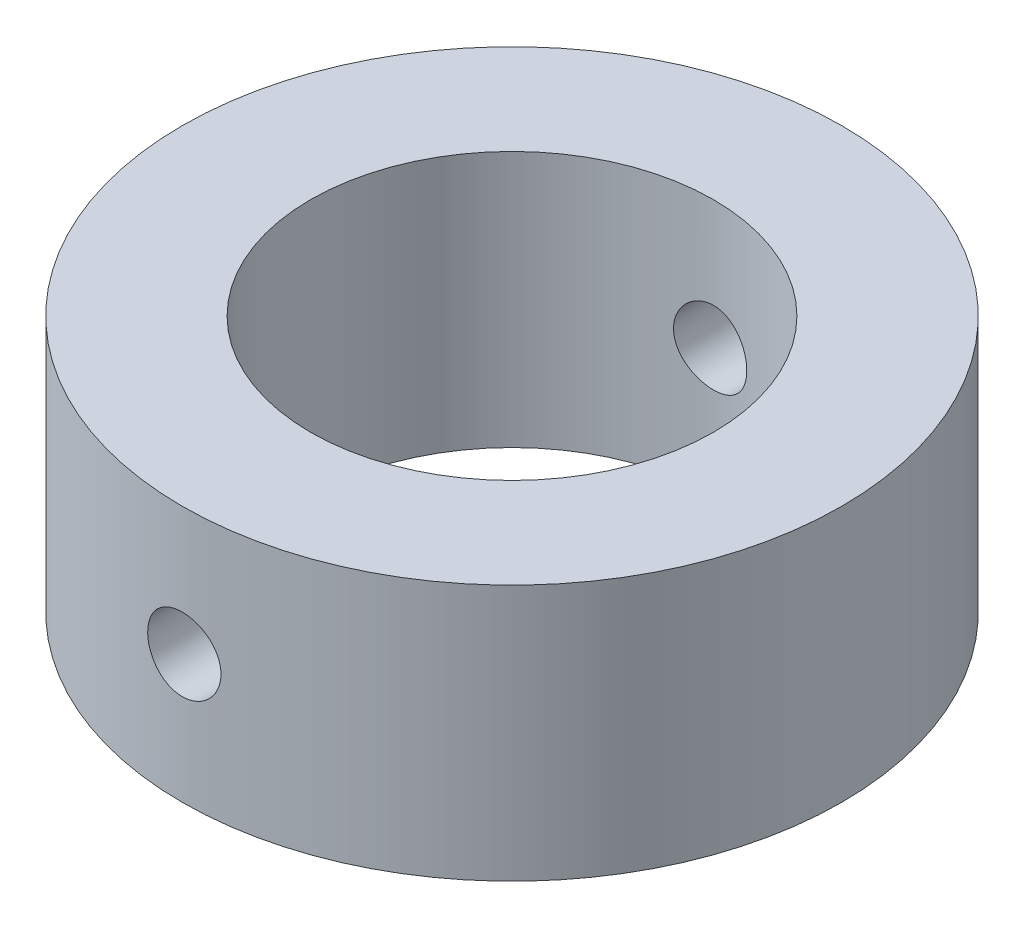
SolidWorks part; units mm, degrees
ref_plane "Front Plane" through (0, 0, 0) normal (0, 0, 1) x (1, 0, 0)
ref_plane "Top Plane" through (0, 0, 0) normal (0, 1, 0) x (1, 0, 0)
ref_plane "Right Plane" through (0, 0, 0) normal (1, 0, 0) x (0, 0, -1)
sketch "Sketch1" plane through (0, 0, 0) normal (0, 0, 1) x (1, 0, 0)
  line L0 (-2.184, 0) -> (25.368, 0) construction
  line L1 (0, -7.728) -> (0, 16.688) construction
  line L3 (18, -7) -> (11, -7)
  line L4 (18, -7) -> (18, 7)
  line L5 (18, 7) -> (11, 7)
  line L6 (11, -7) -> (11, 7)
  line L7 (18, -7) -> (11, 7) construction
  line L8 (18, 7) -> (11, -7) construction
  point P5 (14.5, 0)
  dimension "D1" = 14
  dimension "D2" = 18
  dimension "D3" = 11
revolve "Revolve1" add sketch "Sketch1" angle 360 about L1
sketch "Sketch2" plane through (0, 0, 0) normal (0, 0, 1) x (1, 0, 0)
  circle A0 centre (0, 0) radius 2
  dimension "D1" = 4
extrude "Cut-Extrude1" cut sketch "Sketch2" along normal blind 25 and the other way blind 26
